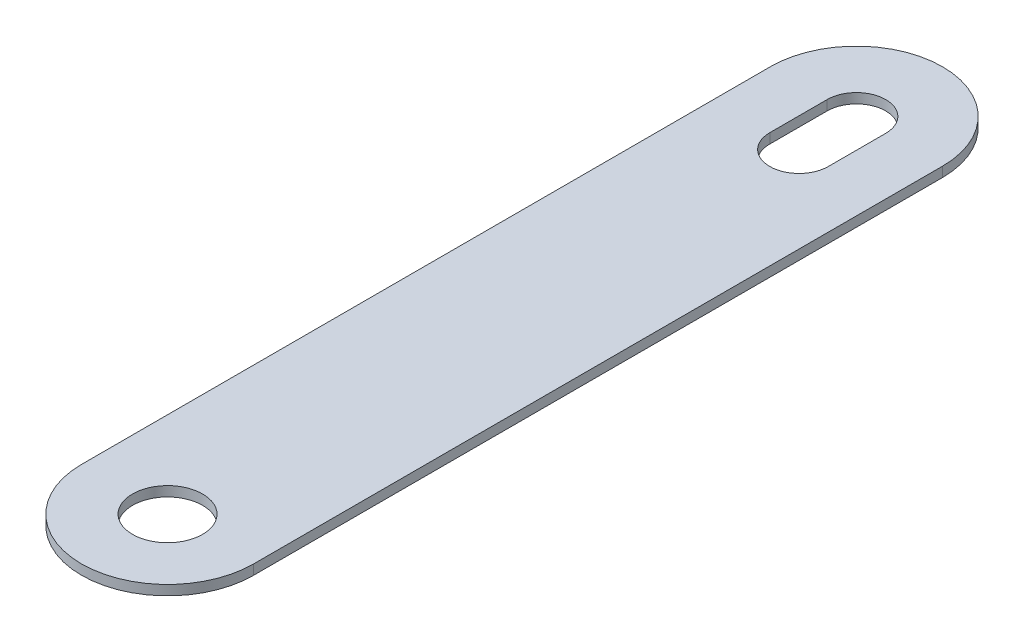
SolidWorks part; units mm, degrees
ref_plane "Front Plane" through (0, 0, 0) normal (0, 0, 1) x (1, 0, 0)
ref_plane "Top Plane" through (0, 0, 0) normal (0, 1, 0) x (1, 0, 0)
ref_plane "Right Plane" through (0, 0, 0) normal (1, 0, 0) x (0, 0, -1)
sketch "Sketch1" plane through (0, 0, 0) normal (0, 1, 0) x (1, 0, 0)
  line L0 (0, 0) -> (0, 60) construction
  line L1 (-7.5, 0) -> (-7.5, 60)
  line L2 (7.5, 0) -> (7.5, 60)
  line L3 (0, 60) -> (0, 55) construction
  line L4 (2.55, 60) -> (2.55, 55)
  line L5 (-2.55, 60) -> (-2.55, 55)
  circle A0 centre (0, 0) radius 3.05
  arc A1 (-7.5, 0) -> (7.5, 0) centre (0, 0) ccw
  arc A2 (7.5, 60) -> (-7.5, 60) centre (0, 60) ccw
  arc A3 (2.55, 60) -> (-2.55, 60) centre (0, 60) ccw
  arc A4 (-2.55, 55) -> (2.55, 55) centre (0, 55) ccw
  point P4 (0, 30)
  point P11 (0, 57.5)
  point P16 (-2.55, 57.5)
  dimension "D1" = 6.1
  dimension "D2" = 15
  dimension "D3" = 60
  dimension "D4" = 5.1
  dimension "D5" = 5
extrude "Boss-Extrude1" add sketch "Sketch1" along normal blind 0.86
